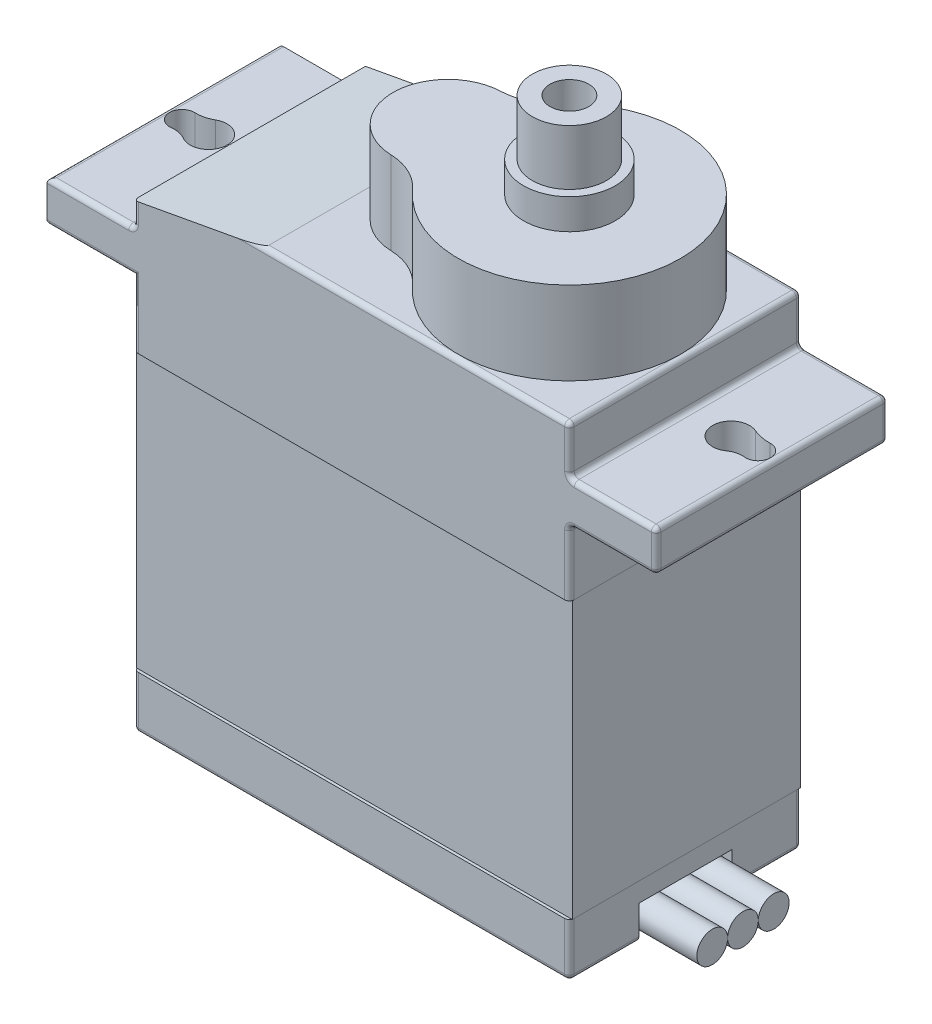
SolidWorks part; units mm, degrees
ref_plane "Alzado" through (0, 0, 0) normal (0, 0, 1) x (1, 0, 0)
ref_plane "Planta" through (0, 0, 0) normal (0, 1, 0) x (1, 0, 0)
ref_plane "Vista lateral" through (0, 0, 0) normal (1, 0, 0) x (0, 0, -1)
sketch "Croquis1" plane through (0, 0, 0) normal (0, 1, 0) x (1, 0, 0)
  line L1 (-11.335, 6.03) -> (11.335, 6.03)
  line L2 (-11.335, 6.03) -> (-11.335, -6.03)
  line L3 (-11.335, -6.03) -> (11.335, -6.03)
  line L4 (11.335, 6.03) -> (11.335, -6.03)
  line L5 (-11.335, 6.03) -> (11.335, -6.03) construction
  line L6 (-11.335, -6.03) -> (11.335, 6.03) construction
  point P0 (0, 0)
  dimension "D1" = 22.67
  dimension "D2" = 12.06
extrude "Saliente-Extruir1" add sketch "Croquis1" along normal blind 25.15
sketch "Croquis2" plane through (11.335, 0, 0) normal (1, 0, 0) x (0, 0, -1)
  line L0 (-6.03, 0) -> (-6.03, 20.53) construction
  line L1 (-6.03, 25.15) -> (-6.03, 0) construction
  line L2 (-6.03, 20.53) -> (6.03, 20.53)
  line L3 (6.03, 25.15) -> (6.03, 0) construction
  line L4 (-6.03, 22.66) -> (6.03, 22.66)
  line L5 (-6.03, 22.66) -> (-6.03, 20.53)
  line L6 (6.03, 22.66) -> (6.03, 20.53)
  dimension "D1" = 20.53
  dimension "D2" = 2.13
extrude "Saliente-Extruir2" add sketch "Croquis2" along normal blind 4.51
sketch "Croquis5" plane through (-11.335, 0, 0) normal (-1, 0, 0) x (0, 0, 1)
  line L1 (6.03, 25.15) -> (6.03, 0) construction
  line L2 (-6.03, 22.66) -> (6.03, 22.66)
  line L3 (-6.03, 22.66) -> (-6.03, 20.53)
  line L4 (-6.03, 20.53) -> (6.03, 20.53)
  line L5 (6.03, 22.66) -> (6.03, 20.53)
  line L8 (-6.03, 0) -> (6.03, 0) construction
  dimension "D1" = 20.53
extrude "Saliente-Extruir3" add sketch "Croquis5" along normal blind 4.51
fillet "Redondeo1" radius 0.25 30 edges at (11.335, 0, 0) (0, 0, -6.03) (0, 0, 6.03) (-11.335, 0, 0) (0, 25.15, -6.03) (0, 25.15, 6.03) (-11.335, 25.15, 0) (11.335, 25.15, 0) (15.845, 21.595, -6.03) (15.845, 21.595, 6.03) (15.845, 20.53, 0) (15.845, 22.66, 0) (-15.845, 20.53, 0) (-15.845, 22.66, 0)
sketch "Croquis6" plane through (0, 22.66, 0) normal (0, 1, 0) x (1, 0, 0)
  line L0 (-15.595, 6.03) -> (-11.585, -5.78) construction
  line L1 (-11.585, -5.78) -> (-11.585, 6.03) construction
  line L2 (-11.585, 6.03) -> (-15.595, -5.78) construction
  line L3 (0, 0) -> (0, 5.78) construction
  line L4 (11.085, 5.78) -> (-11.085, 5.78) construction
  line L5 (0, 5.78) -> (0, -5.78) construction
  line L6 (-11.085, -5.78) -> (11.085, -5.78) construction
  line L9 (-15.595, 6.03) -> (-15.595, -5.78) construction
  arc A0 (-14.0754, -0.7033) -> (-14.0683, 0.9574) centre (-13.59, 0.125) ccw
  arc A1 (14.1493, -0.6553) -> (13.9681, 1.0074) centre (13.59, 0.125) cw
  arc A2 (-14.9216, 0.7478) -> (-14.8659, -0.5415) centre (-14.9475, 0.1009) ccw
  arc A3 (14.8717, -0.4691) -> (14.9323, 0.8213) centre (14.9475, 0.1739) ccw
  arc A4 (-14.9216, 0.7478) -> (-14.0683, 0.9574) centre (-14.8582, 2.332) ccw
  arc A5 (-14.8659, -0.5415) -> (-14.0754, -0.7033) centre (-14.7082, -1.7831) cw
  arc A6 (13.9681, 1.0074) -> (14.9323, 0.8213) centre (14.8781, 3.1309) ccw
  arc A7 (14.1493, -0.6553) -> (14.8717, -0.4691) centre (14.7507, -1.4944) cw
  dimension "D1" = 1.92
  dimension "D2" = 0.6475
  dimension "D3" = 0.6475
extrude "Cortar-Extruir12" cut sketch "Croquis6" against normal blind 4.51
sketch "Croquis8" plane through (0, 25.15, 0) normal (0, 1, 0) x (1, 0, 0)
  line L0 (11.085, 0) -> (-11.085, 0) construction
  line L3 (11.085, -5.78) -> (11.085, 5.78) construction
  line L4 (-11.085, 5.78) -> (-11.085, -5.78) construction
  line L5 (11.085, 5.78) -> (-11.085, 5.78) construction
  line L6 (11.085, 0) -> (-1.015, 0) construction
  arc A0 (0.9947, -3.8509) -> (0.9947, 3.8509) centre (5.305, 0) ccw
  arc A1 (-1.1194, 2.8581) -> (-1.1194, -2.8581) centre (-1.015, 0) ccw
  arc A2 (-1.1194, -2.8581) -> (0.9947, -3.8509) centre (-1.2281, -5.8368) cw
  arc A3 (-1.1194, 2.8581) -> (0.9947, 3.8509) centre (-1.2281, 5.8368) ccw
  dimension "D1" = 5.72
  dimension "D2" = 6.32
extrude "Saliente-Extruir4" add sketch "Croquis8" along normal blind 4.32 separate body
sketch "Croquis9" plane through (0, 29.47, 0) normal (0, 1, 0) x (1, 0, 0)
  line L0 (5.305, 5.78) -> (5.305, 0) construction
  line L1 (11.085, 5.78) -> (-11.085, 5.78) construction
  arc A0 (0.9947, -3.8509) -> (0.9947, 3.8509) centre (5.305, 0) ccw construction
  circle A1 centre (5.305, 0) radius 2.385
  dimension "D1" = 4.77
extrude "Saliente-Extruir5" add sketch "Croquis9" along normal blind 1.58 separate body
sketch "Croquis10" plane through (0, 31.05, 0) normal (0, 1, 0) x (1, 0, 0)
  circle A0 centre (5.305, 0) radius 2.385
extrude "Saliente-Extruir6" add sketch "Croquis10" along normal blind 2.88 separate body
sketch "Croquis11" plane through (0, 33.93, 0) normal (0, 1, 0) x (1, 0, 0)
  circle A0 centre (5.305, 0) radius 1.01
  dimension "D1" = 2.02
extrude "Cortar-Extruir13" cut sketch "Croquis11" against normal blind 3.88
sketch "Croquis12" plane through (0, 33.93, 0) normal (0, 1, 0) x (1, 0, 0)
  circle A2 centre (5.305, 0) radius 1.925
  circle A3 centre (5.305, 0) radius 2.385
  dimension "D4" = 3.85
extrude "Cortar-Extruir14" cut sketch "Croquis12" along a picked direction on the side against the normal blind 2.88
sketch "Croquis13" plane through (0, 0, 6.03) normal (0, 0, 1) x (1, 0, 0)
  line L0 (-4.5405, 25.15) -> (-11.335, 23.905) construction
  line L1 (-11.085, 25.15) -> (11.085, 25.15) construction
  line L2 (-11.335, 22.91) -> (-11.335, 24.9) construction
  line L3 (-4.5405, 25.15) -> (-11.335, 23.905)
  line L4 (-11.335, 23.905) -> (-11.335, 25.15)
  line L5 (-11.335, 25.15) -> (-4.5405, 25.15)
extrude "Cortar-Extruir15" cut sketch "Croquis13" against normal blind 16.88
sketch "Croquis14" plane through (0, 0, 6.03) normal (0, 0, 1) x (1, 0, 0)
  line L0 (-11.085, 17.1) -> (11.085, 17.1)
  line L1 (-11.085, 20.78) -> (-11.085, 0.25) construction
  line L2 (11.085, 0.25) -> (11.085, 20.28) construction
  line L3 (11.085, 24.9) -> (-5.9049, 24.9) construction
  line L4 (-11.085, 2.77) -> (11.085, 2.77)
  line L5 (-11.085, 0.25) -> (11.085, 0.25) construction
  line L6 (11.085, 17.1) -> (11.085, 2.77)
  line L7 (-11.085, 17.1) -> (-11.085, 2.77)
  dimension "D1" = 7.8
  dimension "D2" = 2.52
extrude "Cortar-Extruir16" cut sketch "Croquis14" against normal blind 16.88
sketch "Croquis16" plane through (-11.335, 0, 0) normal (-1, 0, 0) x (0, 0, 1)
  line L0 (5.78, 17.1096) -> (-5.78, 17.1096)
  line L3 (5.78, 0.25) -> (5.78, 20.53) construction
  line L4 (-5.78, 20.53) -> (-5.78, 0.25) construction
  line L5 (-5.78, 2.7548) -> (5.78, 2.7548)
  line L6 (5.78, 17.1096) -> (5.78, 2.7548)
  line L7 (-5.78, 2.7548) -> (-5.78, 17.1096)
extrude "Cortar-Extruir17" cut sketch "Croquis16" against normal blind 27.88
sketch "Croquis17" plane through (0, 0, 0) normal (0, 0, 1) x (1, 0, 0)
  line L0 (-11.335, 17.1096) -> (11.335, 17.1096)
  line L1 (11.335, 17.1096) -> (11.335, 2.7548)
  line L2 (11.335, 2.7548) -> (-11.335, 2.7548)
  line L3 (-11.335, 2.7548) -> (-11.335, 17.1096)
extrude "Cortar-Extruir18" cut sketch "Croquis17" against normal blind 27.88 and the other way blind 27.88
sketch "Croquis18" plane through (0, 0, 0) normal (0, 0, 1) x (1, 0, 0)
  line L0 (-11.335, 17.1096) -> (-11.335, 2.7548)
  line L1 (-11.335, 2.7548) -> (11.335, 2.7548)
  line L2 (11.335, 2.7548) -> (11.335, 17.1096)
  line L3 (11.335, 17.1096) -> (-11.335, 17.1096)
extrude "Saliente-Extruir7" add sketch "Croquis18" along normal blind 5.88 and the other way blind 6 separate body
sketch "Croquis19" plane through (11.335, 0, 0) normal (1, 0, 0) x (0, 0, -1)
  line L0 (5.78, 1.5024) -> (2.42, 1.5024) construction
  line L1 (5.78, 0.25) -> (5.78, 2.7548) construction
  line L2 (0, 2.7548) -> (0, 1.7548) construction
  line L4 (-5.78, 1.5024) -> (-2.42, 1.5024) construction
  line L5 (6, 2.7548) -> (-5.88, 2.7548) construction
  line L6 (-2.42, 1.7548) -> (2.42, 1.7548)
  line L7 (2.42, 1.7548) -> (2.42, 0)
  line L8 (5.78, 0) -> (-5.78, 0) construction
  line L9 (2.42, 0) -> (-2.42, 0)
  line L10 (-2.42, 0) -> (-2.42, 1.7548)
  dimension "D1" = 3.36
  dimension "D2" = 1
extrude "Cortar-Extruir19" cut sketch "Croquis19" against normal blind 1.6
sketch "Croquis20" plane through (9.735, 0, 0) normal (1, 0, 0) x (0, 0, -1)
  line L0 (0, 1.7548) -> (0, 0) construction
  line L1 (2.42, 1.7548) -> (-2.42, 1.7548) construction
  line L2 (0, 0.8774) -> (2.42, 0.8774) construction
  line L3 (2.42, 0) -> (2.42, 1.7548) construction
  line L4 (0, 0.8774) -> (-2.42, 0.8774) construction
  line L5 (-2.42, 1.7548) -> (-2.42, 0) construction
  circle A0 centre (0, 0.8774) radius 0.8
  circle A1 centre (-1.6, 0.8774) radius 0.8
  circle A2 centre (1.6, 0.8774) radius 0.8
  dimension "D1" = 1.6
  dimension "D2" = 1.6
  dimension "D3" = 1.6
extrude "Saliente-Extruir8" add sketch "Croquis20" along normal blind 4.6 separate body contours A1 | A0 | A2
